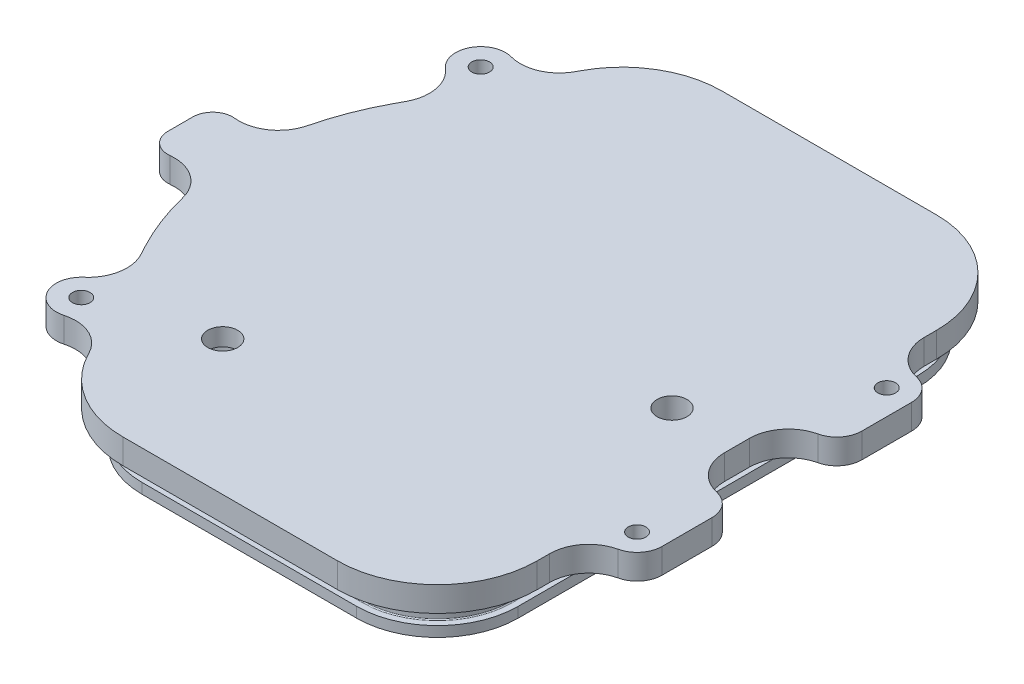
SolidWorks part; units mm, degrees
material "6061-T6 (SS)"
ref_plane "Front Plane" through (0, 0, 0) normal (0, 0, 1) x (1, 0, 0)
ref_plane "Top Plane" through (0, 0, 0) normal (0, 1, 0) x (1, 0, 0)
ref_plane "Right Plane" through (0, 0, 0) normal (1, 0, 0) x (0, 0, -1)
sketch "Sketch1" plane through (0, 0, 0) normal (0, 1, 0) x (1, 0, 0)
  line L64 (-10.16, -76.2) -> (44.45, -76.2)
  line L65 (69.85, -50.8) -> (69.85, 50.8)
  line L66 (44.45, 76.2) -> (-10.16, 76.2)
  line L67 (-32.5718, 62.7529) -> (-49.3059, 31.3765)
  line L68 (-49.3059, -31.3765) -> (-32.5718, -62.7529)
  line L69 (-10.16, -76.2) -> (44.45, -76.2)
  line L70 (69.85, -50.8) -> (69.85, 50.8)
  line L71 (44.45, 76.2) -> (-10.16, 76.2)
  line L72 (-32.5718, 62.7529) -> (-49.3059, 31.3765)
  line L73 (-49.3059, -31.3765) -> (-32.5718, -62.7529)
  arc A68 (44.45, -76.2) -> (69.85, -50.8) centre (44.45, -50.8) ccw
  arc A69 (69.85, 50.8) -> (44.45, 76.2) centre (44.45, 50.8) ccw
  arc A70 (-10.16, 76.2) -> (-32.5718, 62.7529) centre (-10.16, 50.8) ccw
  arc A72 (-32.5718, -62.7529) -> (-10.16, -76.2) centre (-10.16, -50.8) ccw
  arc A73 (44.45, -76.2) -> (69.85, -50.8) centre (44.45, -50.8) ccw
  arc A74 (69.85, 50.8) -> (44.45, 76.2) centre (44.45, 50.8) ccw
  arc A75 (-10.16, 76.2) -> (-32.5718, 62.7529) centre (-10.16, 50.8) ccw
  arc A77 (-32.5718, -62.7529) -> (-10.16, -76.2) centre (-10.16, -50.8) ccw
  arc A89 (-49.3059, 31.3765) -> (-49.3059, -31.3765) centre (9.525, 0) ccw
  arc A90 (-49.3059, 31.3765) -> (-49.3059, -31.3765) centre (9.525, 0) ccw
  dimension "D1" = 4.445
extrude "Boss-Extrude1" add sketch "Sketch1" along normal blind 6.35
sketch "Sketch2" plane through (0, 0, 0) normal (0, -1, 0) x (1, 0, 0)
  line L5 (-28.2911, 60.4699) -> (-45.0252, 29.0935)
  line L6 (-28.2911, 60.4699) -> (-45.0252, 29.0935)
  line L7 (-45.0252, -29.0935) -> (-28.2911, -60.4699)
  line L8 (-45.0252, -29.0935) -> (-28.2911, -60.4699)
  line L9 (-10.16, -71.3486) -> (44.45, -71.3486)
  line L10 (-10.16, -71.3486) -> (44.45, -71.3486)
  line L11 (64.9986, -50.8) -> (64.9986, 50.8)
  line L12 (64.9986, -50.8) -> (64.9986, 50.8)
  line L13 (44.45, 71.3486) -> (-10.16, 71.3486)
  line L14 (44.45, 71.3486) -> (-10.16, 71.3486)
  arc A5 (-10.16, 71.3486) -> (-28.2911, 60.4699) centre (-10.16, 50.8) ccw
  arc A6 (-10.16, 71.3486) -> (-28.2911, 60.4699) centre (-10.16, 50.8) ccw
  arc A7 (-45.0252, 29.0935) -> (-45.0252, -29.0935) centre (9.525, 0) ccw
  arc A8 (-45.0252, 29.0935) -> (-45.0252, -29.0935) centre (9.525, 0) ccw
  arc A9 (-28.2911, -60.4699) -> (-10.16, -71.3486) centre (-10.16, -50.8) ccw
  arc A10 (-28.2911, -60.4699) -> (-10.16, -71.3486) centre (-10.16, -50.8) ccw
  arc A11 (44.45, -71.3486) -> (64.9986, -50.8) centre (44.45, -50.8) ccw
  arc A12 (44.45, -71.3486) -> (64.9986, -50.8) centre (44.45, -50.8) ccw
  arc A13 (64.9986, 50.8) -> (44.45, 71.3486) centre (44.45, 50.8) ccw
  arc A14 (64.9986, 50.8) -> (44.45, 71.3486) centre (44.45, 50.8) ccw
  dimension "D1" = 4.8514
extrude "Boss-Extrude2" add sketch "Sketch2" along normal blind 8.7122
sketch "Sketch3" plane through (0, 0, 0) normal (0, -1, 0) x (1, 0, 0)
  line L4 (-82.55, -82.55) -> (82.55, -82.55)
  line L5 (-82.55, -82.55) -> (-82.55, 82.55)
  line L7 (-26.7223, 59.6332) -> (-43.4564, 28.2568)
  line L8 (-26.7223, 59.6332) -> (-43.4564, 28.2568)
  line L9 (-43.4564, -28.2568) -> (-26.7223, -59.6332)
  line L10 (-43.4564, -28.2568) -> (-26.7223, -59.6332)
  line L11 (-10.16, -69.5706) -> (44.45, -69.5706)
  line L12 (-82.55, 82.55) -> (82.55, 82.55)
  line L13 (82.55, -82.55) -> (82.55, 82.55)
  line L14 (-82.55, -82.55) -> (82.55, 82.55) construction
  line L15 (-82.55, 82.55) -> (82.55, -82.55) construction
  line L16 (-10.16, -69.5706) -> (44.45, -69.5706)
  line L17 (63.2206, -50.8) -> (63.2206, 50.8)
  line L18 (63.2206, -50.8) -> (63.2206, 50.8)
  line L19 (44.45, 69.5706) -> (-10.16, 69.5706)
  line L20 (44.45, 69.5706) -> (-10.16, 69.5706)
  arc A5 (-10.16, 69.5706) -> (-26.7223, 59.6332) centre (-10.16, 50.8) ccw
  arc A6 (-10.16, 69.5706) -> (-26.7223, 59.6332) centre (-10.16, 50.8) ccw
  arc A7 (-43.4564, 28.2568) -> (-43.4564, -28.2568) centre (9.525, 0) ccw
  arc A8 (-43.4564, 28.2568) -> (-43.4564, -28.2568) centre (9.525, 0) ccw
  arc A9 (-26.7223, -59.6332) -> (-10.16, -69.5706) centre (-10.16, -50.8) ccw
  arc A10 (-26.7223, -59.6332) -> (-10.16, -69.5706) centre (-10.16, -50.8) ccw
  arc A11 (44.45, -69.5706) -> (63.2206, -50.8) centre (44.45, -50.8) ccw
  arc A12 (44.45, -69.5706) -> (63.2206, -50.8) centre (44.45, -50.8) ccw
  arc A13 (63.2206, 50.8) -> (44.45, 69.5706) centre (44.45, 50.8) ccw
  arc A14 (63.2206, 50.8) -> (44.45, 69.5706) centre (44.45, 50.8) ccw
  dimension "D2" = 165.1
  dimension "D3" = 165.1
  dimension "D1" = 6.6294
extrude "Cut-Extrude1" cut sketch "Sketch3" along normal blind 3.556 from offset 2.54
sketch "Sketch4" plane through (0, 0, 0) normal (0, -1, 0) x (1, 0, 0)
  circle A0 centre (0, 0) radius 25.4
  circle A1 centre (0, 0) radius 19.05
  dimension "D2" = 50.8
  dimension "D1" = 6.35
extrude "Boss-Extrude3" add sketch "Sketch4" along normal up to surface (8.7122 mm away) up to face at (5.0169, -8.7122, 0)
hole_wizard "Hole1" positions "Sketch6" profile "Sketch5" legacy end condition through all
sketch "Sketch6" plane through (0, -8.7122, 0) normal (0, -1, 0) x (1, 0, 0)
  line L0 (0, 0) -> (-50000, 0) construction
  point P0 (53.34, 0)
  dimension "D1" = 53.34
sketch "Sketch5" plane through (53.34, -8.7122, 0) normal (1, 0, 0) x (0, 0, -1)
  line L0 (0, 0) -> (0, 15.0622)
  line L1 (0, 15.0622) -> (3.81, 15.0622)
  line L2 (3.81, 15.0622) -> (3.81, 0)
  line L5 (3.81, 0) -> (0, 0)
  line L11 (0, -6.35) -> (0, 107.95) construction
  dimension "Thru Hole Dia." = 7.62
  dimension "Thru Hole Depth" = 15.0622
sketch "Sketch7" plane through (0, -8.7122, 0) normal (0, -1, 0) x (1, 0, 0)
  line L5 (58.6486, 8.6628) -> (58.6486, 50.8)
  line L10 (-22.6882, 57.4817) -> (-39.4223, 26.1052)
  line L11 (-39.4223, -26.1052) -> (-22.6882, -57.4817)
  line L12 (-10.16, -64.9986) -> (44.45, -64.9986)
  line L13 (58.6486, -50.8) -> (58.6486, 50.8)
  line L14 (44.45, 64.9986) -> (-10.16, 64.9986)
  line L15 (-22.6882, 57.4817) -> (-39.4223, 26.1052)
  line L16 (-39.4223, -26.1052) -> (-22.6882, -57.4817)
  line L17 (-10.16, -64.9986) -> (44.45, -64.9986)
  line L18 (58.6486, -50.8) -> (58.6486, -8.6628)
  line L19 (44.45, 64.9986) -> (-10.16, 64.9986)
  arc A5 (-39.4223, 26.1052) -> (-39.4223, -26.1052) centre (9.525, 0) ccw
  arc A6 (-39.4223, 26.1052) -> (-39.4223, -26.1052) centre (9.525, 0) ccw
  circle A9 centre (53.34, 0) radius 10.16
  arc A10 (58.6486, 8.6628) -> (58.6486, -8.6628) centre (53.34, 0) ccw
  arc A12 (-10.16, 64.9986) -> (-22.6882, 57.4817) centre (-10.16, 50.8) ccw
  arc A14 (-22.6882, -57.4817) -> (-10.16, -64.9986) centre (-10.16, -50.8) ccw
  arc A15 (44.45, -64.9986) -> (58.6486, -50.8) centre (44.45, -50.8) ccw
  arc A16 (58.6486, 50.8) -> (44.45, 64.9986) centre (44.45, 50.8) ccw
  arc A17 (-10.16, 64.9986) -> (-22.6882, 57.4817) centre (-10.16, 50.8) ccw
  arc A19 (-22.6882, -57.4817) -> (-10.16, -64.9986) centre (-10.16, -50.8) ccw
  arc A20 (44.45, -64.9986) -> (58.6486, -50.8) centre (44.45, -50.8) ccw
  arc A21 (58.6486, 50.8) -> (44.45, 64.9986) centre (44.45, 50.8) ccw
  dimension "D1" = 6.35
  dimension "D2" = 6.35
extrude "Cut-Extrude2" cut sketch "Sketch7" against normal offset from surface (10.6172 mm away) 4.445 up to face at (53.34, 6.35, -3.81)
hole_wizard "Hole2" positions "Sketch10" profile "Sketch9" legacy end condition through all
sketch "Sketch10" plane through (0, 1.905, 0) normal (0, -1, 0) x (1, 0, 0)
  line L0 (0, 0) -> (-50000, 0) construction
  point P0 (-19.05, 41.91)
  dimension "D1" = 19.05
  dimension "D2" = 41.91
sketch "Sketch9" plane through (-19.05, 1.905, 41.91) normal (1, 0, 0) x (0, 0, -1)
  line L0 (0, 0) -> (0, 4.445)
  line L1 (0, 4.445) -> (3.81, 4.445)
  line L2 (3.81, 4.445) -> (3.81, 0)
  line L5 (3.81, 0) -> (0, 0)
  line L11 (0, -6.35) -> (0, 107.95) construction
  dimension "Thru Hole Dia." = 7.62
  dimension "Thru Hole Depth" = 4.445
sketch "Sketch11" plane through (0, 1.905, 0) normal (0, -1, 0) x (1, 0, 0)
  line L0 (-22.6882, 57.4817) -> (-39.4223, 26.1052) construction
  line L3 (-10.16, 33.02) -> (-35.7344, 33.02)
  line L4 (-7.62, 30.48) -> (-7.62, 64.9986)
  line L5 (-7.62, 30.48) -> (-37.0891, 30.48)
  line L6 (-10.16, 58.42) -> (-10.16, 33.02)
  line L8 (-35.7344, 33.02) -> (-37.0891, 30.48)
  line L9 (-10.16, 33.02) -> (-37.0891, 33.02) construction
  line L11 (-22.1406, 58.42) -> (-10.16, 58.42)
  line L12 (44.45, 64.9986) -> (-10.16, 64.9986) construction
  line L13 (-10.16, 67.1621) -> (-10.16, 33.02) construction
  line L14 (-7.62, 64.9986) -> (-10.16, 64.9986)
  line L19 (0, 0) -> (-50000, 0) construction
  line L20 (-7.62, 67.1621) -> (-7.62, 30.48) construction
  arc A1 (-10.16, 64.9986) -> (-22.6882, 57.4817) centre (-10.16, 50.8) ccw construction
  arc A2 (-10.16, 64.9986) -> (-22.1406, 58.42) centre (-10.16, 50.8) ccw
  point P0 (-19.05, 41.91)
  point P2 (-41.5233, 16.1586)
  point P11 (-3.175, -15.875)
  point P18 (-3.175, 15.875)
  dimension "D1" = 8.89
  dimension "D2" = 11.43
  dimension "D5" = 16.51
  dimension "D3" = 2.54
extrude "Boss-Extrude4" add sketch "Sketch11" along normal up to surface (10.6172 mm away) up to face at (13.3965, -8.7122, 0)
fillet "Fillet4" radius 6.604 4 edges at (-10.16, -3.4036, 58.42) (-10.16, -3.4036, 33.02) (-35.7344, -3.4036, 33.02) (-22.1406, -3.4036, 58.42)
fillet "Fillet5" radius 7.62 4 edges at (-7.62, -3.4036, 64.9986) (-37.0891, -3.4036, 30.48) (58.6486, -3.4036, -8.6628) (58.6486, -3.4036, 8.6628)
sketch "Sketch12" plane through (0, 0, 0) normal (0, -1, 0) x (1, 0, 0)
  line L0 (82.55, -19.05) -> (82.55, -31.75)
  line L1 (69.85, 47.625) -> (69.85, 3.175)
  line L2 (-33.0698, -61.8191) -> (-48.011, -33.8044)
  line L3 (0, 0) -> (-50000, 0) construction
  line L4 (-48.011, 33.8044) -> (-33.0698, 61.8191)
  line L5 (82.55, 19.05) -> (82.55, 31.75)
  line L6 (69.85, -47.625) -> (69.85, -3.175)
  line L7 (69.85, 50.8) -> (69.85, -50.8) construction
  line L8 (-71.755, 3.175) -> (-71.755, -3.175)
  arc A0 (-33.0698, -61.8191) -> (-44.4579, -56.9222) centre (-41.8244, -66.4882) ccw construction
  arc A1 (-50.2886, -45.9897) -> (-44.4579, -56.9222) centre (-46.1433, -50.8) ccw construction
  arc A2 (-50.2886, -45.9897) -> (-48.011, -33.8044) centre (-56.7656, -38.4735) ccw construction
  arc A3 (82.55, 31.75) -> (77.5939, 37.9451) centre (76.2, 31.75) ccw
  arc A4 (77.5939, 37.9451) -> (69.85, 47.625) centre (79.7719, 47.625) cw
  arc A5 (77.5939, -12.8549) -> (69.85, -3.175) centre (79.7719, -3.175) cw
  arc A6 (82.55, -19.05) -> (77.5939, -12.8549) centre (76.2, -19.05) ccw
  arc A7 (77.5939, -37.9451) -> (69.85, -47.625) centre (79.7719, -47.625) ccw
  arc A8 (82.55, -31.75) -> (77.5939, -37.9451) centre (76.2, -31.75) cw
  arc A9 (-44.4579, 56.9222) -> (-33.0698, 61.8191) centre (-41.8244, 66.4882) ccw construction
  arc A10 (-44.4579, 56.9222) -> (-50.2886, 45.9897) centre (-46.1433, 50.8) ccw construction
  arc A11 (-48.011, 33.8044) -> (-50.2886, 45.9897) centre (-56.7656, 38.4735) ccw construction
  arc A12 (-33.0698, -61.8191) -> (-44.4579, -56.9222) centre (-41.8244, -66.4882) ccw
  arc A13 (-50.2886, -45.9897) -> (-44.4579, -56.9222) centre (-46.1433, -50.8) ccw
  arc A14 (-50.2886, -45.9897) -> (-48.011, -33.8044) centre (-56.7656, -38.4735) ccw
  arc A21 (-44.4579, 56.9222) -> (-33.0698, 61.8191) centre (-41.8244, 66.4882) ccw
  arc A22 (-44.4579, 56.9222) -> (-50.2886, 45.9897) centre (-46.1433, 50.8) ccw
  arc A23 (-48.011, 33.8044) -> (-50.2886, 45.9897) centre (-56.7656, 38.4735) ccw
  arc A24 (82.55, 19.05) -> (77.5939, 12.8549) centre (76.2, 19.05) cw
  arc A25 (77.5939, 12.8549) -> (69.85, 3.175) centre (79.7719, 3.175) ccw
  arc A27 (-55.2325, 15.875) -> (-55.2325, -15.875) centre (9.525, 0) ccw
  arc A28 (-49.3059, 31.3765) -> (-49.3059, -31.3765) centre (9.525, 0) ccw construction
  arc A29 (-55.2325, 15.875) -> (-66.1339, 8.2261) centre (-65.0564, 18.2833) cw
  arc A30 (-66.1339, 8.2261) -> (-71.755, 3.175) centre (-66.675, 3.175) ccw
  arc A31 (-66.1339, -8.2261) -> (-55.2325, -15.875) centre (-65.0564, -18.2833) cw
  arc A35 (-71.755, -3.175) -> (-66.1339, -8.2261) centre (-66.675, -3.175) ccw
  dimension "D3" = 6.35
  dimension "D5" = 6.35
  dimension "D6" = 5.08
  dimension "D1" = 6.35
  dimension "D2" = 12.7
  dimension "D10" = 44.45
  dimension "D4" = 31.75
  dimension "D7" = 31.75
  dimension "D8" = 81.28
  dimension "D9" = 6.35
extrude "Boss-Extrude5" add sketch "Sketch12" against normal blind 6.35
fillet "Fillet6" radius 9.144 1 edges at (-7.62, -3.4036, 30.48)
chamfer "Chamfer2" distance 1.016 angle 45 26 edges at (-17.4947, -8.7122, 58.42) (-12.0943, -8.7122, 56.4857) (-10.16, -8.7122, 45.72) (43.18, -8.7122, 0) (-7.62, -8.7122, 48.5013) (-24.6405, -8.7122, 30.48) (-10.2982, -8.7122, 33.1582) (-12.0943, -8.7122, 34.9543) (-20.7459, -8.7122, 33.02) (-30.3906, -8.7122, 36.2263) (-27.3036, -8.7122, 48.8278) (58.6486, -8.7122, 34.2146) (54.4899, -8.7122, 60.8399) (22.225, -8.7122, 64.9986) (-5.3882, -8.7122, 62.7668) (58.6486, -8.7122, -34.2146) (54.4899, -8.7122, -60.8399) (-36.4375, -8.7122, 29.3941) (17.145, -8.7122, -64.9986) (-45.9486, -8.7122, 0) (-17.4651, -8.7122, -62.9752) (-31.0552, -8.7122, -41.7935) (56.7563, -8.7122, 12.6034) (56.7563, -8.7122, -12.6034) (-39.3315, -8.7122, 26.2756) (-21.6231, -8.7122, 57.4789)
fillet "Fillet7" radius 0.254 20 edges at (-19.8174, -6.096, 66.8957) (17.145, -6.096, 69.5706) (57.7228, -6.096, 64.0728) (63.2206, -6.096, 0) (57.7228, -6.096, -64.0728) (17.145, -6.096, -69.5706) (-19.8174, -6.096, -66.8957) (-35.0894, -6.096, -43.945) (-50.5206, -6.096, 0) (-19.8174, -2.54, 66.8957) (17.145, -2.54, 69.5706) (57.7228, -2.54, 64.0728) (63.2206, -2.54, 0) (57.7228, -2.54, -64.0728) (17.145, -2.54, -69.5706) (-19.8174, -2.54, -66.8957) (-35.0894, -2.54, -43.945) (-50.5206, -2.54, 0) (-35.0894, -6.096, 43.945) (-35.0894, -2.54, 43.945)
hole_wizard "#8 Clearance Hole1" positions "Sketch14" profile "Sketch13" hole size "#8" standard "Ansi Inch" end condition through all
sketch "Sketch14" plane through (0, 6.35, 0) normal (0, 1, 0) x (-1, 0, 0)
  arc A5 (50.2886, 45.9897) -> (44.4579, 56.9222) centre (46.1433, 50.8) ccw construction
  arc A6 (44.4579, -56.9222) -> (50.2886, -45.9897) centre (46.1433, -50.8) ccw construction
  arc A7 (-82.55, -31.75) -> (-77.5939, -37.9451) centre (-76.2, -31.75) ccw construction
  arc A8 (-77.5939, 37.9451) -> (-82.55, 31.75) centre (-76.2, 31.75) ccw construction
  point P0 (46.1433, 50.8)
  point P1 (46.1433, -50.8)
  point P4 (-76.2, -31.75)
  point P7 (-76.2, 31.75)
sketch "Sketch13" plane through (-46.1433, 6.35, 50.8) normal (1, 0, 0) x (0, 0, 1)
  line L0 (0, 0) -> (0, 15.0622)
  line L1 (0, 15.0622) -> (2.2479, 15.0622)
  line L2 (2.2479, 15.0622) -> (2.2479, 0)
  line L5 (2.2479, 0) -> (0, 0)
  line L11 (0, -6.35) -> (0, 107.95) construction
  dimension "Thru Hole Dia." = 4.4958
  dimension "Thru Hole Depth" = 15.0622
